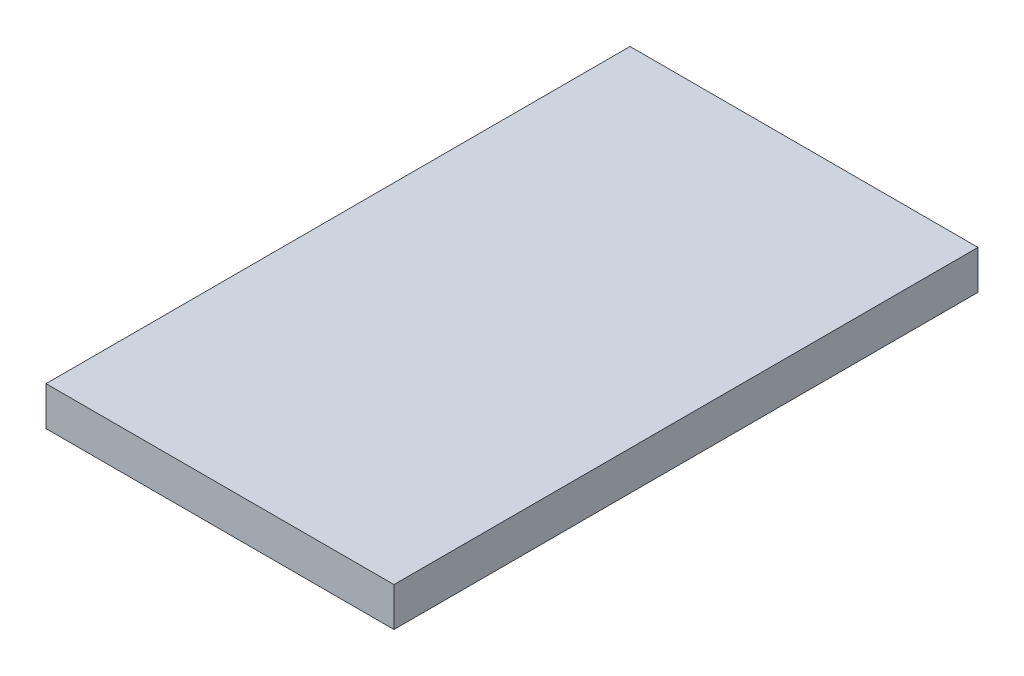
SolidWorks part; units mm, degrees
ref_plane "Front Plane" through (0, 0, 0) normal (0, 0, 1) x (1, 0, 0)
ref_plane "Top Plane" through (0, 0, 0) normal (0, 1, 0) x (1, 0, 0)
ref_plane "Right Plane" through (0, 0, 0) normal (1, 0, 0) x (0, 0, -1)
sketch "Sketch1" plane through (0, 0, 0) normal (0, 1, 0) x (1, 0, 0)
  line L1 (-46.3855, 250.3143) -> (135.2245, 250.3143)
  line L2 (-46.3855, 250.3143) -> (-46.3855, -54.4857)
  line L3 (-46.3855, -54.4857) -> (135.2245, -54.4857)
  line L4 (135.2245, 250.3143) -> (135.2245, -54.4857)
  point P4 (0, 0)
  point P5 (0, 0)
  dimension "D1" = 181.61
  dimension "D2" = 304.8
extrude "Boss-Extrude1" add sketch "Sketch1" along normal blind 20.32
